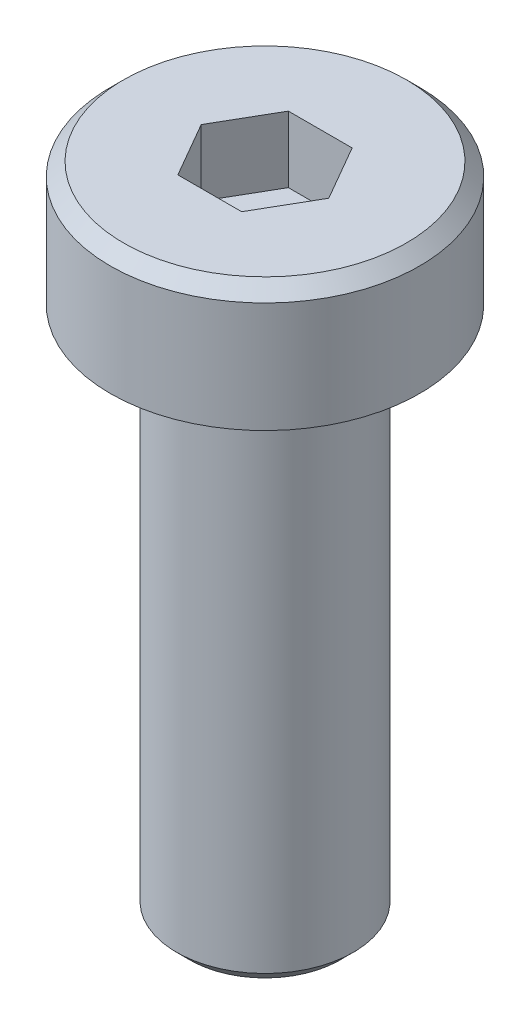
SolidWorks part; units mm, degrees
ref_plane "前视基准面" through (0, 0, 0) normal (0, 0, 1) x (1, 0, 0)
ref_plane "上视基准面" through (0, 0, 0) normal (0, 1, 0) x (1, 0, 0)
ref_plane "右视基准面" through (0, 0, 0) normal (1, 0, 0) x (0, 0, -1)
other "Configuration Table"
sketch "轴向轮廓" plane through (0, 0, 0) normal (0, 0, 1) x (1, 0, 0)
  line L0 (0, -12) -> (1.7, -12)
  line L1 (1.7, -12) -> (2, -11.7)
  line L2 (2, -11.7) -> (2, 0)
  line L3 (2, 0) -> (3.5, 0)
  line L4 (3.5, 0) -> (3.5, 2.5)
  line L5 (3.5, 2.5) -> (3.2, 2.8)
  line L6 (3.2, 2.8) -> (0, 2.8)
  line L7 (0, 2.8) -> (0, -12)
  line L8 (0, -14) -> (0, 4.8) construction
revolve "螺钉外形_旋转" add sketch "轴向轮廓" angle 360 about L8
sketch "内六角轮廓" plane through (0, 2.8, 0) normal (0, 1, 0) x (1, 0, 0)
  line L0 (1.4434, 0) -> (0.7217, 1.25)
  line L1 (0.7217, 1.25) -> (-0.7217, 1.25)
  line L2 (-0.7217, 1.25) -> (-1.4434, 0)
  line L3 (-1.4434, 0) -> (-0.7217, -1.25)
  line L4 (-0.7217, -1.25) -> (0.7217, -1.25)
  line L5 (0.7217, -1.25) -> (1.4434, 0)
extrude "内六角" cut sketch "内六角轮廓" against normal blind 1.5
